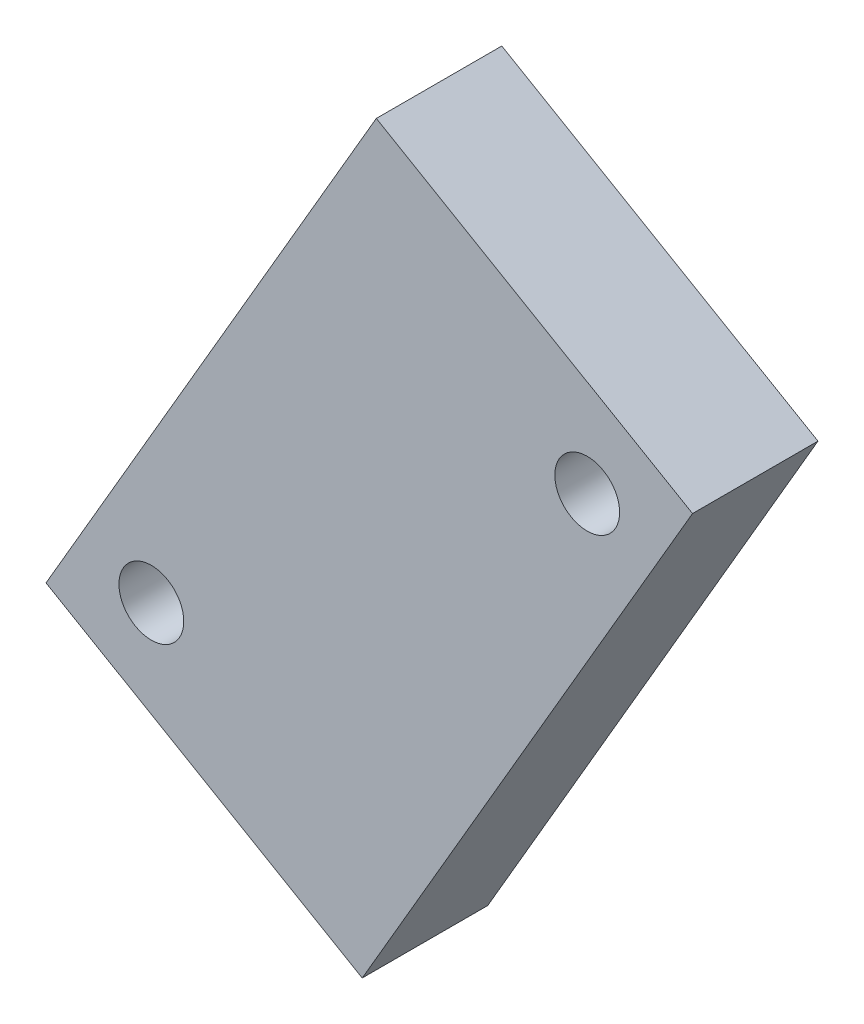
SolidWorks part; units mm, degrees
ref_plane "Płaszczyzna przednia" through (0, 0, 0) normal (0, 0, 1) x (1, 0, 0)
ref_plane "Płaszczyzna górna" through (0, 0, 0) normal (0, 1, 0) x (1, 0, 0)
ref_plane "Płaszczyzna prawa" through (0, 0, 0) normal (1, 0, 0) x (0, 0, -1)
sketch "Szkic1" plane through (0, 0, 0) normal (0, 0, 1) x (1, 0, 0)
  line L4 (437.4999, 37.4386) -> (452.624, 28.6345)
  line L5 (452.624, 28.6345) -> (468.4211, 55.7714)
  line L6 (468.4211, 55.7714) -> (453.2971, 64.5755)
  line L7 (453.2971, 64.5755) -> (437.4999, 37.4386)
  line L8 (437.4999, 37.4386) -> (452.624, 28.6345)
  line L9 (452.624, 28.6345) -> (468.4211, 55.7714)
  line L10 (468.4211, 55.7714) -> (453.2971, 64.5755)
  line L11 (453.2971, 64.5755) -> (437.4999, 37.4386)
  dimension "D1" = 0
extrude "Dodanie-wyciągnięcie1" add sketch "Szkic1" along normal blind 6
sketch "Szkic2" plane through (0, 0, 6) normal (0, 0, 1) x (1, 0, 0)
  circle A0 centre (463.3839, 54.0753) radius 1.55 construction
  circle A1 centre (463.3839, 54.0753) radius 1.55
  circle A2 centre (442.5371, 39.1347) radius 1.55 construction
  circle A3 centre (442.5371, 39.1347) radius 1.55
extrude "Wytnij-wyciągnięcie1" cut sketch "Szkic2" against normal blind 6
